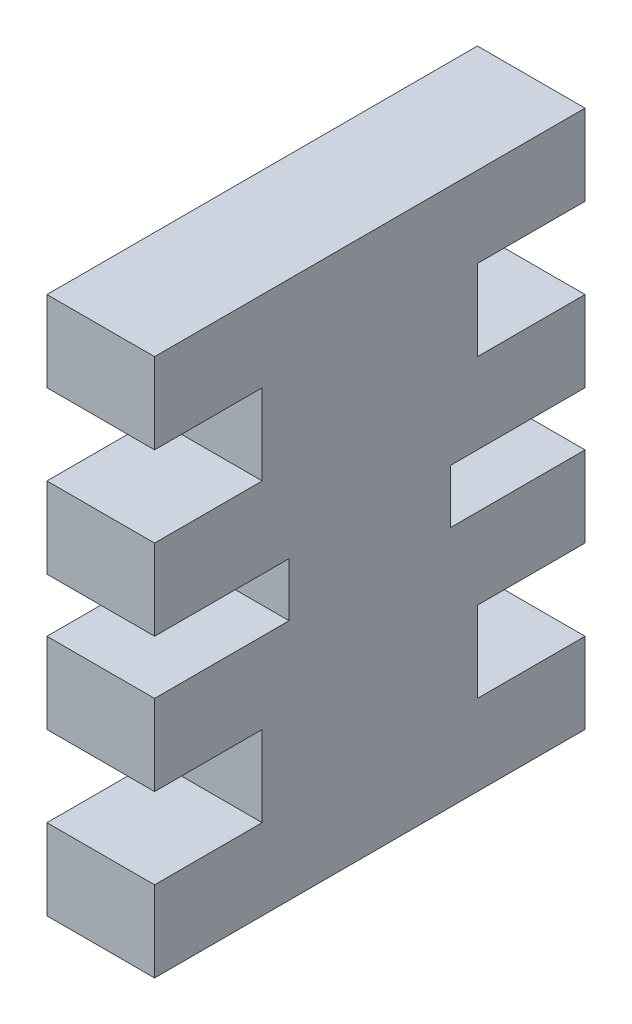
SolidWorks part; units mm, degrees
ref_plane "Front Plane" through (0, 0, 0) normal (0, 0, 1) x (1, 0, 0)
ref_plane "Top Plane" through (0, 0, 0) normal (0, 1, 0) x (1, 0, 0)
ref_plane "Right Plane" through (0, 0, 0) normal (1, 0, 0) x (0, 0, -1)
sketch "Sketch2" plane through (0, 0, 0) normal (1, 0, 0) x (0, 0, -1)
  line L0 (0, 0) -> (80, 0)
  line L1 (80, 0) -> (80, 15)
  line L2 (80, 15) -> (60, 15)
  line L3 (60, 15) -> (60, 30)
  line L4 (60, 30) -> (80, 30)
  line L5 (80, 30) -> (80, 45)
  line L6 (80, 45) -> (55, 45)
  line L7 (55, 45) -> (55, 55)
  line L8 (55, 55) -> (80, 55)
  line L9 (80, 55) -> (80, 70)
  line L10 (80, 70) -> (60, 70)
  line L11 (60, 70) -> (60, 85)
  line L12 (60, 85) -> (80, 85)
  line L13 (80, 85) -> (80, 100)
  line L14 (80, 100) -> (0, 100)
  line L15 (40, 142.2552) -> (40, -59.1748) construction
  line L16 (0, 0) -> (0, 15)
  line L17 (0, 85) -> (0, 100)
  line L18 (25, 45) -> (25, 55)
  line L19 (0, 45) -> (25, 45)
  line L20 (25, 55) -> (0, 55)
  line L21 (20, 85) -> (0, 85)
  line L22 (20, 70) -> (20, 85)
  line L23 (0, 70) -> (20, 70)
  line L24 (0, 55) -> (0, 70)
  line L25 (0, 30) -> (0, 45)
  line L26 (20, 30) -> (0, 30)
  line L27 (20, 15) -> (20, 30)
  line L28 (0, 15) -> (20, 15)
extrude "Boss-Extrude1" add sketch "Sketch2" against normal blind 20
